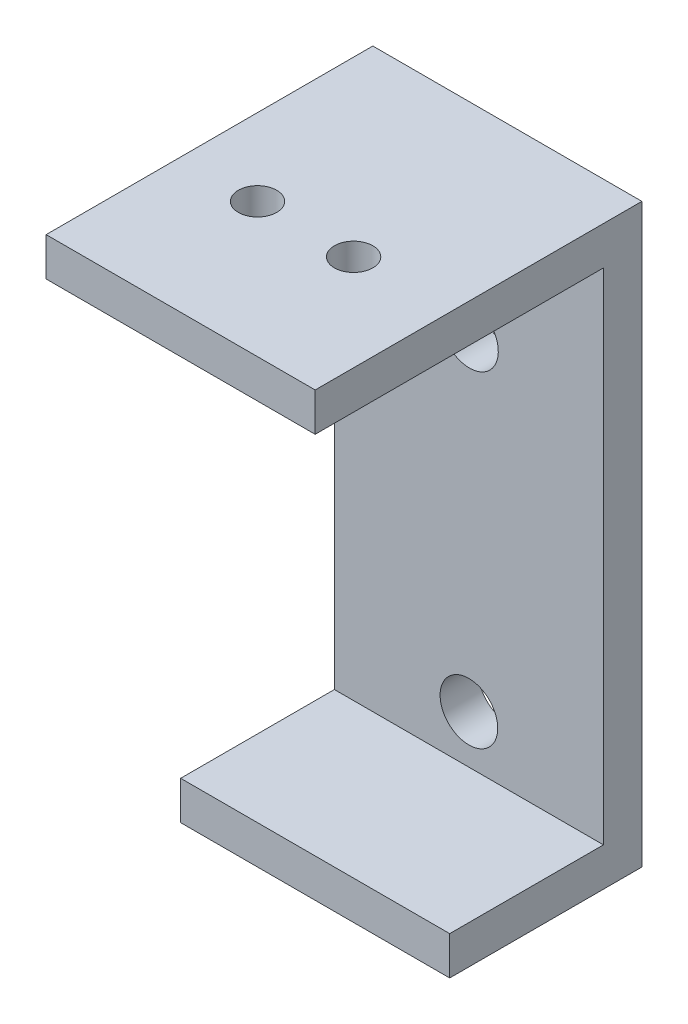
SolidWorks part; units mm, degrees
ref_plane "前视基准面" through (0, 0, 0) normal (0, 0, 1) x (1, 0, 0)
ref_plane "上视基准面" through (0, 0, 0) normal (0, 1, 0) x (1, 0, 0)
ref_plane "右视基准面" through (0, 0, 0) normal (1, 0, 0) x (0, 0, -1)
other "Configuration Table"
sketch "草图1" plane through (0, 0, 0) normal (1, 0, 0) x (0, 0, -1)
  line L0 (0, 0) -> (10, 0)
  line L1 (10, 0) -> (10, 30)
  line L2 (10, 30) -> (-7, 30)
  line L3 (-7, 30) -> (-7, 28)
  line L4 (-7, 28) -> (8, 28)
  line L5 (8, 28) -> (8, 2)
  line L6 (8, 2) -> (0, 2)
  line L7 (0, 2) -> (0, 0)
  dimension "D1" = 10
  dimension "D2" = 2
  dimension "D3" = 2
  dimension "D4" = 2
  dimension "D5" = 26
  dimension "D6" = 17
extrude "凸台-拉伸1" add sketch "草图1" along normal blind 14
sketch3d "3D草图4"
  line L4 (0, 0, -10) -> (0, 30, -10)
  line L5 (0, 30, -10) -> (14, 30, -10)
  line L6 (14, 30, -10) -> (14, 0, -10)
  line L7 (14, 0, -10) -> (0, 0, -10)
  line L8 (0, 0, -10) -> (0, 30, -10)
  line L9 (0, 30, -10) -> (14, 30, -10)
  line L10 (14, 30, -10) -> (14, 0, -10)
  line L11 (14, 0, -10) -> (0, 0, -10)
  dimension "D1" = 10
  dimension "D2" = 0
sketch "草图5" plane through (0, 0, -10) normal (0, 0, -1) x (-1, 0, 0)
  line L0 (-14, 0) -> (0, 30)
  line L1 (-14, 30) -> (0, 0)
  line L2 (-7, 15) -> (0, 15) construction
  line L3 (0, 0) -> (0, 30) construction
  line L4 (-7, 15) -> (-7, 0) construction
  line L5 (-14, 0) -> (0, 0) construction
  line L6 (-7, 15) -> (-14, 15) construction
  line L7 (-14, 30) -> (-14, 0) construction
  line L8 (-7.0515, 14.8897) -> (-7, 30) construction
  line L9 (0, 30) -> (-14, 30) construction
  circle A0 centre (-7, 4.5) radius 1.5
  circle A1 centre (-7.029, 21.5) radius 1.5
  dimension "D1" = 17
  dimension "D2" = 4.5
extrude "切除-拉伸1" cut sketch "草图5" against normal blind 14 contours A1 | A0
sketch3d "3D草图5" plane through (0, 0, 0) normal (0, 0, 1) x (1, 0, 0)
  dimension "D1" = 10
sketch "草图6" plane through (0, 30, 0) normal (0, 1, 0) x (1, 0, 0)
  line L1 (0, 10) -> (0, -7) construction
  line L3 (14, -7) -> (0, -7) construction
  circle A0 centre (4, 0) radius 1
  circle A1 centre (9, 0) radius 1
  dimension "D1" = 7
  dimension "D2" = 4
  dimension "D3" = 5
extrude "切除-拉伸2" cut sketch "草图6" against normal blind 14
